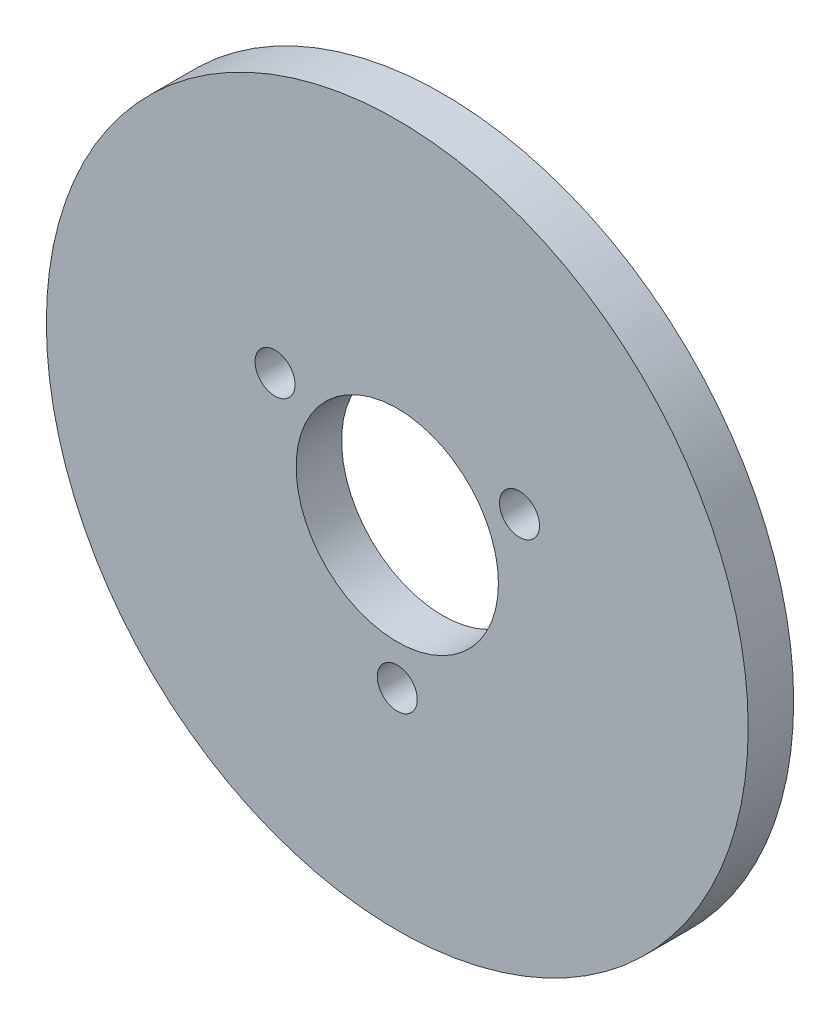
SolidWorks part; units mm, degrees
material "ABS PC"
ref_plane "Front Plane" through (0, 0, 0) normal (0, 0, 1) x (1, 0, 0)
ref_plane "Top Plane" through (0, 0, 0) normal (0, 1, 0) x (1, 0, 0)
ref_plane "Right Plane" through (0, 0, 0) normal (1, 0, 0) x (0, 0, -1)
sketch "Sketch1" plane through (0, 0, 0) normal (0, 0, 1) x (1, 0, 0)
  circle A0 centre (0, 0) radius 22.375
  circle A1 centre (0, 0) radius 6.45
  dimension "D1" = 44.75
  dimension "D2" = 12.9
extrude "Boss-Extrude1" add sketch "Sketch1" along normal blind 2.9
sketch "Sketch2" plane through (0, 0, 0) normal (0, 0, -1) x (-1, 0, 0)
  circle A1 centre (7.7942, 4.5) radius 1.275
  circle A2 centre (7.7942, 4.5) radius 1.275
  circle A3 centre (-7.7942, 4.5) radius 1.275
  circle A4 centre (-7.7942, 4.5) radius 1.275
  circle A5 centre (0, -9) radius 1.275
  circle A6 centre (0, -9) radius 1.275
  dimension "D1" = 0
  dimension "D2" = 0
  dimension "D3" = 0
extrude "Cut-Extrude1" cut sketch "Sketch2" against normal through all
equation "\"smallPulleyTeeth\"= 15"
equation "\"largePulleyTeeth\"= 30"
equation "\"eighthThick\"= 2.9mm"
equation "\"sixteenthThick\" = 1.7mm"
equation "\"wheelEighthThick\"=3.0mm"
equation "\"quarterThick\"=5.9mm"
equation "\"bushingDiam\"= 7.85mm"
equation "\"plateBoltCircle\"= 65mm"
equation "\"plateBoltDiam\"= 5mm"
equation "\"D1@Boss-Extrude1\"=\"eighthThick\""
